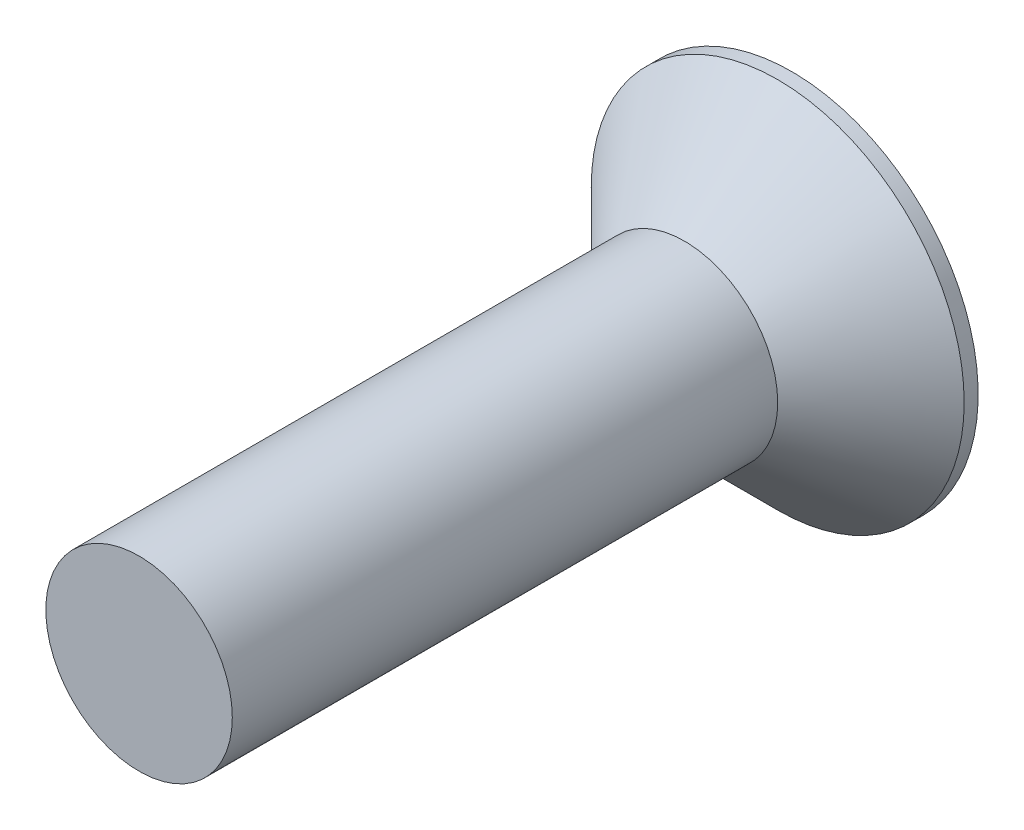
SolidWorks part; units mm, degrees
material "Chrome Stainless Steel"
ref_plane "Front Plane" through (0, 0, 0) normal (0, 0, 1) x (1, 0, 0)
ref_plane "Top Plane" through (0, 0, 0) normal (0, 1, 0) x (1, 0, 0)
ref_plane "Right Plane" through (0, 0, 0) normal (1, 0, 0) x (0, 0, -1)
sketch "Sketch1" plane through (0, 0, 0) normal (0, 0, 1) x (1, 0, 0)
  circle A0 centre (0, 0) radius 2
  dimension "OD" = 4
extrude "Extrude1" add sketch "Sketch1" against normal blind 14
sketch "Sketch6" plane through (0, 0, -14) normal (0, 0, -1) x (-1, 0, 0)
  circle A0 centre (0, 0) radius 4
  dimension "head dia" = 8
extrude "Extrude2" add sketch "Sketch6" against normal blind 2.3
sketch "Sketch10" plane through (0, 0, 0) normal (1, 0, 0) x (0, 0, -1)
  line L0 (13.7, -4) -> (11.7, -2)
  line L1 (11.7, -2) -> (11.7, -4)
  line L2 (13.7, -4) -> (11.7, -4)
  line L3 (0, 0) -> (11.7, 0) construction
  line L4 (11.7, 4) -> (11.7, -4) construction
  line L8 (11.7, 4) -> (11.7, -4) construction
  line L9 (11.7, 2) -> (11.7, -2) construction
  dimension "D1" = 45
revolve "Cut-Revolve2" cut sketch "Sketch10" angle 360 about L3
sketch "Sketch7" plane through (0, 0, -14) normal (0, 0, 1) x (1, 0, 0)
  line L1 (0, 1.4434) -> (-1.25, 0.7217)
  line L2 (-1.25, 0.7217) -> (-1.25, -0.7217)
  line L3 (-1.25, -0.7217) -> (0, -1.4434)
  line L4 (0, -1.4434) -> (1.25, -0.7217)
  line L5 (1.25, -0.7217) -> (1.25, 0.7217)
  line L6 (1.25, 0.7217) -> (0, 1.4434)
  circle A0 centre (0, 0) radius 1.25 construction
  dimension "hex dia" = 2.5
extrude "Cut-Extrude1" cut sketch "Sketch7" along normal blind 1.875
equation "\"D1@Cut-Extrude1\" = \"hex dia@Sketch7\"*.75"
